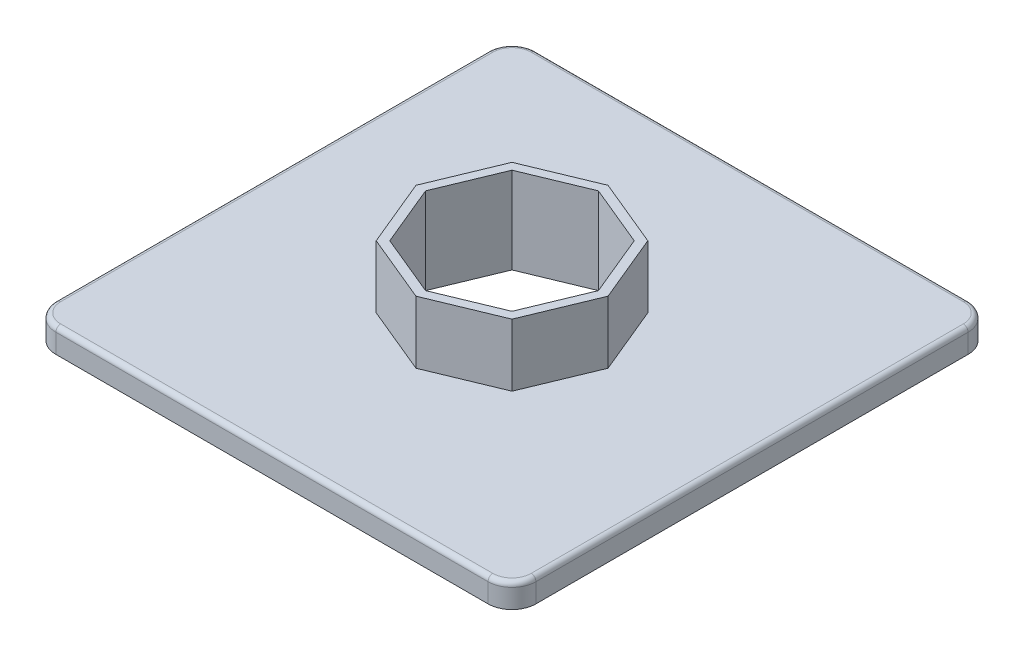
SolidWorks part; units mm, degrees
ref_plane "Front Plane" through (0, 0, 0) normal (0, 0, 1) x (1, 0, 0)
ref_plane "Top Plane" through (0, 0, 0) normal (0, 1, 0) x (1, 0, 0)
ref_plane "Right Plane" through (0, 0, 0) normal (1, 0, 0) x (0, 0, -1)
sketch "Sketch1" plane through (0, 0, 0) normal (0, 1, 0) x (1, 0, 0)
  line L1 (5, 0) -> (95, 0)
  line L2 (0, 5) -> (0, 95)
  line L3 (5, 100) -> (95, 100)
  line L4 (100, 5) -> (100, 95)
  arc A0 (100, 95) -> (95, 100) centre (95, 95) ccw
  arc A1 (95, 0) -> (100, 5) centre (95, 5) ccw
  arc A2 (5, 0) -> (0, 5) centre (5, 5) cw
  arc A3 (5, 100) -> (0, 95) centre (5, 95) ccw
  point P7 (100, 100)
  point P10 (100, 0)
  point P13 (0, 0)
  dimension "D3" = 5
  dimension "D1" = 100
  dimension "D2" = 100
extrude "Boss-Extrude1" add sketch "Sketch1" along normal blind 5
fillet "Fillet1" radius 1 8 edges at (0, 5, -50) (1.4645, 5, -98.5355) (50, 5, -100) (98.5355, 5, -98.5355) (100, 5, -50) (98.5355, 5, -1.4645) (50, 5, 0) (1.4645, 5, -1.4645)
sketch "Sketch2" plane through (0, 5, 0) normal (0, 1, 0) x (1, 0, 0)
  line L0 (0, 5) -> (0, 95) construction
  line L1 (70, 50) -> (64.1421, 64.1421)
  line L2 (64.1421, 64.1421) -> (50, 70)
  line L3 (50, 70) -> (35.8579, 64.1421)
  line L4 (35.8579, 64.1421) -> (30, 50)
  line L5 (30, 50) -> (35.8579, 35.8579)
  line L6 (35.8579, 35.8579) -> (50, 30)
  line L7 (50, 30) -> (64.1421, 35.8579)
  line L8 (64.1421, 35.8579) -> (70, 50)
  line L9 (5, 100) -> (95, 100) construction
  line L11 (68, 50) -> (62.7279, 62.7279)
  line L12 (62.7279, 62.7279) -> (50, 68)
  line L13 (50, 68) -> (37.2721, 62.7279)
  line L14 (37.2721, 62.7279) -> (32, 50)
  line L15 (32, 50) -> (37.2721, 37.2721)
  line L16 (37.2721, 37.2721) -> (50, 32)
  line L17 (50, 32) -> (62.7279, 37.2721)
  line L18 (62.7279, 37.2721) -> (68, 50)
  circle A0 centre (50, 50) radius 18.4776 construction
  circle A1 centre (50, 50) radius 16.6298 construction
  point P14 (0, 0)
  point P24 (0, 0)
  dimension "D1" = 20
  dimension "D2" = 50
  dimension "D3" = 50
  dimension "D4" = 18
extrude "Boss-Extrude2" add sketch "Sketch2" along normal blind 13
sketch "Sketch5" plane through (0, 5, 0) normal (0, 1, 0) x (1, 0, 0)
  line L0 (5, 100) -> (95, 100) construction
  line L1 (68, 50) -> (62.7279, 62.7279)
  line L2 (62.7279, 62.7279) -> (50, 68)
  line L3 (50, 68) -> (37.2721, 62.7279)
  line L4 (37.2721, 62.7279) -> (32, 50)
  line L5 (32, 50) -> (37.2721, 37.2721)
  line L6 (37.2721, 37.2721) -> (50, 32)
  line L7 (50, 32) -> (62.7279, 37.2721)
  line L8 (62.7279, 37.2721) -> (68, 50)
  line L9 (0, 5) -> (0, 95) construction
  circle A0 centre (50, 50) radius 16.6298 construction
  dimension "D1" = 18
  dimension "D2" = 50
  dimension "D3" = 50
extrude "Cut-Extrude1" cut sketch "Sketch5" against normal through all
